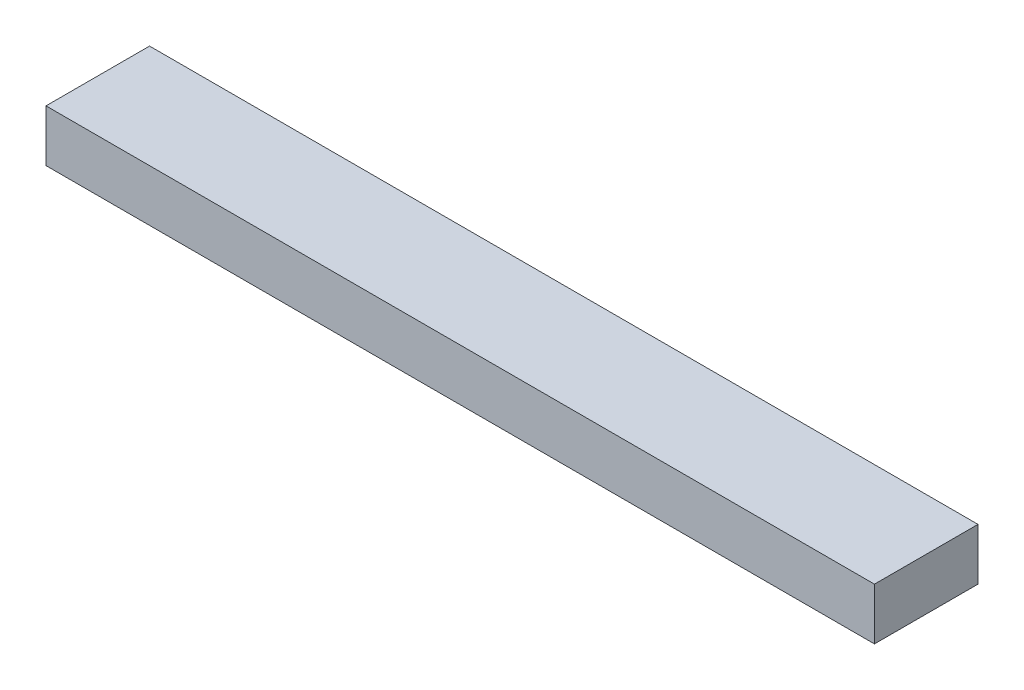
SolidWorks part; units mm, degrees
ref_plane "Front Plane" through (0, 0, 0) normal (0, 0, 1) x (1, 0, 0)
ref_plane "Top Plane" through (0, 0, 0) normal (0, 1, 0) x (1, 0, 0)
ref_plane "Right Plane" through (0, 0, 0) normal (1, 0, 0) x (0, 0, -1)
sketch "Sketch1" plane through (0, 0, 0) normal (0, 1, 0) x (1, 0, 0)
  line L1 (-370.5263, -131.1579) -> (429.4737, -131.1579)
  line L2 (-370.5263, -131.1579) -> (-370.5263, -31.1579)
  line L3 (-370.5263, -31.1579) -> (429.4737, -31.1579)
  line L4 (429.4737, -131.1579) -> (429.4737, -31.1579)
  dimension "D1" = 800
  dimension "D2" = 100
extrude "Boss-Extrude1" add sketch "Sketch1" along normal blind 50
